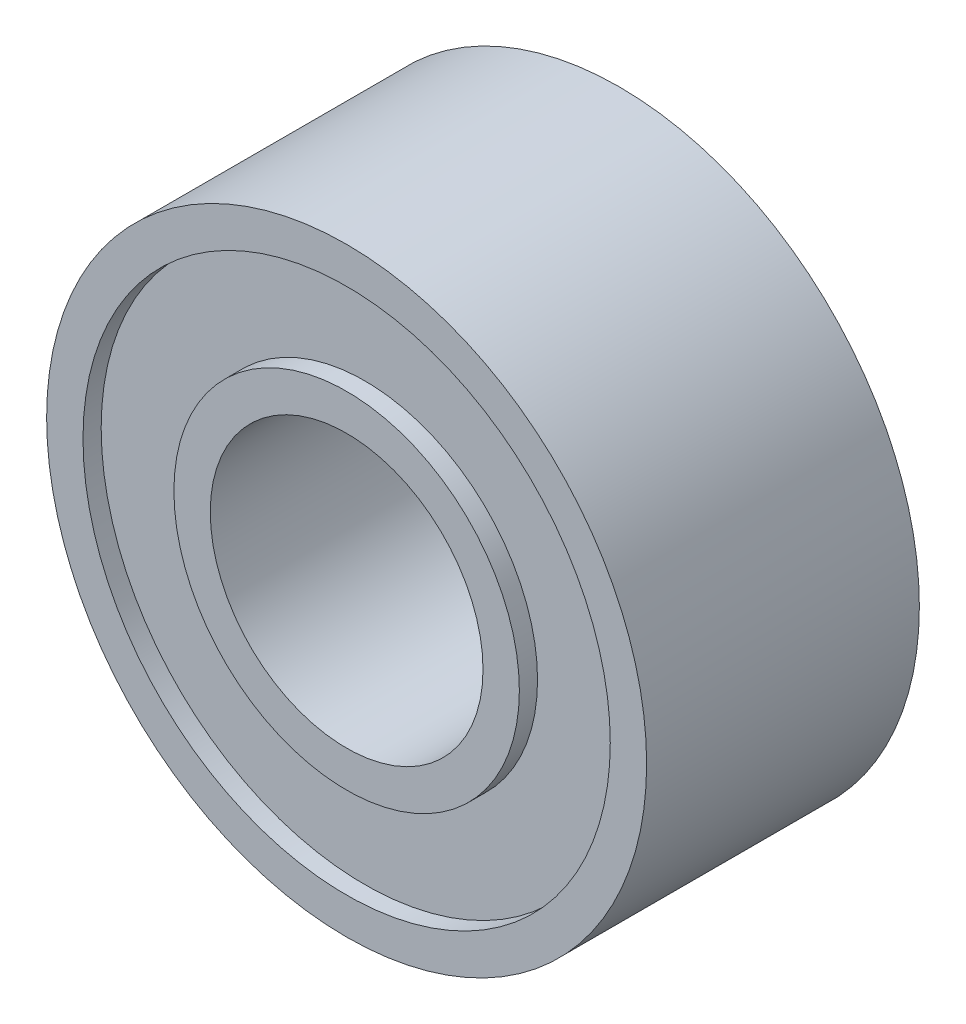
SolidWorks part; units mm, degrees
ref_plane "Front Plane" through (0, 0, 0) normal (0, 0, 1) x (1, 0, 0)
ref_plane "Top Plane" through (0, 0, 0) normal (0, 1, 0) x (1, 0, 0)
ref_plane "Right Plane" through (0, 0, 0) normal (1, 0, 0) x (0, 0, -1)
sketch "Sketch1" plane through (0, 0, 0) normal (0, 0, 1) x (1, 0, 0)
  circle A0 centre (0, 0) radius 7.5
  circle A1 centre (0, 0) radius 9.5
  dimension "D1" = 15
  dimension "D2" = 2
extrude "Boss-Extrude1" add sketch "Sketch1" along normal mid plane 15
sketch "Sketch4" plane through (0, 0, 0) normal (0, 0, 1) x (1, 0, 0)
  circle A0 centre (0, 0) radius 9.5
  circle A2 centre (0, 0) radius 14.5
  dimension "D1" = 19
  dimension "D2" = 5
extrude "Boss-Extrude2" add sketch "Sketch4" along normal mid plane 13
sketch "Sketch5" plane through (0, 0, 0) normal (0, 0, 1) x (1, 0, 0)
  circle A0 centre (0, 0) radius 14.5
  circle A1 centre (0, 0) radius 16.5
  dimension "D1" = 29
  dimension "D2" = 2
extrude "Boss-Extrude3" add sketch "Sketch5" along normal mid plane 15
